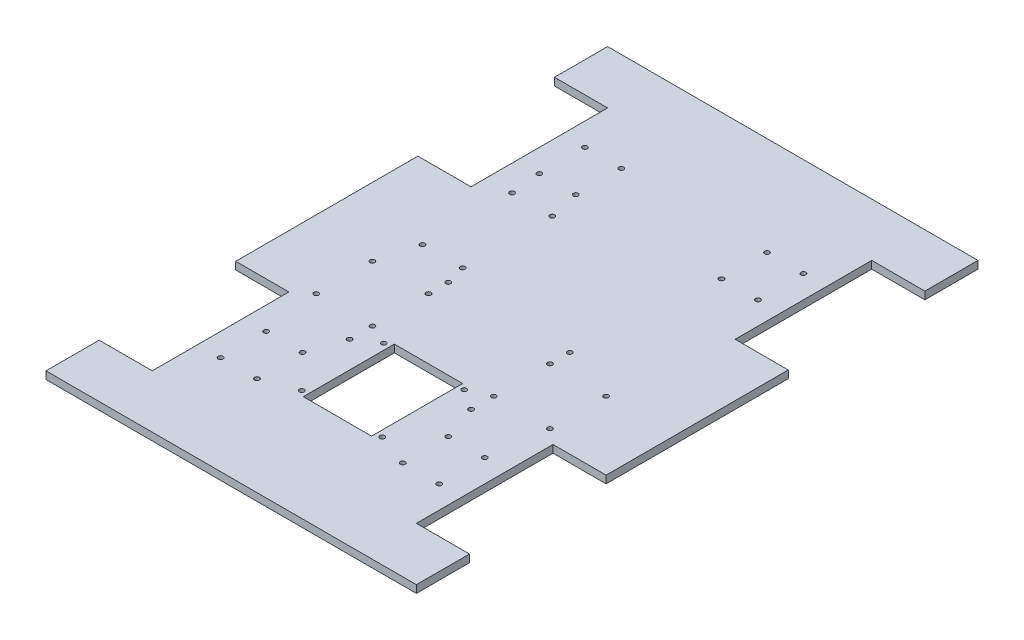
SolidWorks part; units mm, degrees
ref_plane "Front" through (0, 0, 0) normal (0, 0, 1) x (1, 0, 0)
ref_plane "Top" through (0, 0, 0) normal (0, 1, 0) x (1, 0, 0)
ref_plane "Right" through (0, 0, 0) normal (1, 0, 0) x (0, 0, -1)
sketch "草图2" plane through (0, 0, 0) normal (0, 1, 0) x (1, 0, 0)
  line L1 (0, 0) -> (160, 0)
  line L2 (0, 0) -> (0, 250)
  line L3 (0, 250) -> (160, 250)
  line L4 (160, 0) -> (160, 250)
  dimension "D1" = 250
  dimension "D2" = 160
extrude "原型板" add sketch "草图2" along normal blind 5
sketch "轮组位置" plane through (0, 5, 0) normal (0, 1, 0) x (1, 0, 0)
  line L0 (0, 250) -> (0, 0) construction
  line L1 (8, 245) -> (32, 245)
  line L2 (8, 245) -> (8, 215)
  line L3 (8, 215) -> (32, 215)
  line L4 (32, 245) -> (32, 215)
  line L5 (8, 35) -> (32, 35)
  line L6 (8, 35) -> (8, 5)
  line L7 (8, 5) -> (32, 5)
  line L8 (32, 35) -> (32, 5)
  line L9 (128, 245) -> (152, 245)
  line L10 (128, 245) -> (128, 215)
  line L11 (128, 215) -> (152, 215)
  line L12 (152, 245) -> (152, 215)
  line L13 (128, 35) -> (152, 35)
  line L14 (128, 35) -> (128, 5)
  line L15 (128, 5) -> (152, 5)
  line L16 (152, 35) -> (152, 5)
  line L17 (160, 0) -> (160, 250) construction
  line L19 (-11, 262.5) -> (-39, 262.5)
  line L20 (-11, 262.5) -> (-11, 197.5)
  line L21 (-11, 197.5) -> (-39, 197.5)
  line L22 (-39, 262.5) -> (-39, 197.5)
  line L23 (171, 262.5) -> (199, 262.5)
  line L24 (171, 262.5) -> (171, 197.5)
  line L25 (171, 197.5) -> (199, 197.5)
  line L26 (199, 262.5) -> (199, 197.5)
  line L27 (-11, 52.5) -> (-39, 52.5)
  line L28 (-11, 52.5) -> (-11, -12.5)
  line L29 (-11, -12.5) -> (-39, -12.5)
  line L30 (-39, 52.5) -> (-39, -12.5)
  line L31 (199, 52.5) -> (171, 52.5)
  line L32 (199, 52.5) -> (199, -12.5)
  line L33 (199, -12.5) -> (171, -12.5)
  line L34 (171, 52.5) -> (171, -12.5)
  point P24 (8, 230)
  point P25 (-11, 230)
  point P34 (8, 20)
  point P35 (-39, 20)
  point P40 (-25, 262.5)
  point P41 (20, 245)
  point P42 (140, 245)
  point P43 (185, 262.5)
  point P44 (-25, 52.5)
  point P45 (20, 35)
  point P46 (185, 52.5)
  point P47 (140, 35)
  point P49 (-11, 20)
  point P50 (0, 125)
  dimension "D1" = 30
  dimension "D2" = 24
  dimension "D3" = 30
  dimension "D4" = 24
  dimension "D5" = 30
  dimension "D6" = 24
  dimension "D7" = 30
  dimension "D8" = 24
  dimension "D9" = 8
  dimension "D10" = 8
  dimension "D11" = 8
  dimension "D12" = 8
  dimension "D13" = 0
  dimension "D14" = 0
  dimension "D15" = 28
  dimension "D16" = 65
  dimension "D17" = 0
  dimension "D18" = 28
  dimension "D19" = 65
  dimension "D20" = 0
  dimension "D21" = 45
  dimension "D22" = 45
  dimension "D23" = 45
  dimension "D24" = 45
  dimension "D25" = 28
  dimension "D26" = 105
  dimension "D27" = 0
  dimension "D28" = 0
  dimension "D29" = 28
  dimension "D30" = 65
  dimension "385" = 275
  dimension "D31" = 65
sketch "尺寸限制框" plane through (0, 0, 0) normal (0, 1, 0) x (1, 0, 0)
  line L0 (160, 250) -> (0, 250) construction
  line L1 (-55, 295) -> (215, 295)
  line L2 (-55, 295) -> (-55, -45)
  line L3 (-55, -45) -> (215, -45)
  line L4 (215, 295) -> (215, -45)
  line L5 (0, 250) -> (0, 0) construction
  point P4 (80, 295)
  point P7 (80, 250)
  point P8 (-55, 125)
  point P11 (0, 125)
  dimension "D1" = 340
  dimension "D2" = 270
  dimension "D3" = 0
  dimension "D4" = 0
sketch "草图6" plane through (0, 5, 0) normal (0, 1, 0) x (1, 0, 0)
  circle A0 centre (8, 245) radius 1.6
  circle A1 centre (32, 245) radius 1.6
  circle A2 centre (8, 215) radius 1.6
  circle A3 centre (32, 215) radius 1.6
  circle A4 centre (128, 245) radius 1.6
  circle A5 centre (152, 245) radius 1.6
  circle A6 centre (128, 215) radius 1.6
  circle A7 centre (152, 215) radius 1.6
  circle A8 centre (32, 35) radius 1.6
  circle A9 centre (8, 35) radius 1.6
  circle A10 centre (8, 5) radius 1.6
  circle A11 centre (32, 5) radius 1.6
  circle A12 centre (128, 35) radius 1.6
  circle A13 centre (152, 35) radius 1.6
  circle A14 centre (128, 5) radius 1.6
  circle A15 centre (152, 5) radius 1.6
  dimension "D1" = 3.2
  dimension "D2" = 3.2
  dimension "D3" = 3.2
  dimension "D4" = 3.2
  dimension "D5" = 3.2
  dimension "D6" = 3.2
  dimension "D7" = 3.2
  dimension "D8" = 3.2
  dimension "D9" = 3.2
  dimension "D10" = 3.2
  dimension "D11" = 3.2
  dimension "D12" = 3.2
  dimension "D13" = 3.2
  dimension "D14" = 3.2
  dimension "D15" = 3.2
  dimension "D16" = 3.2
extrude "轮组固定" cut sketch "草图6" against normal through all
sketch "草图7" plane through (0, 5, 0) normal (0, 1, 0) x (1, 0, 0)
  line L0 (0, 250) -> (0, 0) construction
  line L1 (160, 0) -> (160, 250) construction
  circle A0 centre (3, 110) radius 1.6
  circle A1 centre (40, 73) radius 1.6
  circle A2 centre (3, 73) radius 1.6
  circle A3 centre (40, 110) radius 1.6
  circle A4 centre (120, 110) radius 1.6
  circle A5 centre (157, 73) radius 1.6
  circle A6 centre (120, 73) radius 1.6
  circle A7 centre (157, 110) radius 1.6
  point P20 (0, 125)
  point P21 (160, 125)
  dimension "D1" = 37
  dimension "D2" = 37
  dimension "D3" = 3
  dimension "D4" = 37
  dimension "D5" = 37
  dimension "D6" = 37
  dimension "D7" = 37
  dimension "D8" = 3
  dimension "D9" = 37
  dimension "D10" = 0
  dimension "D11" = 37
  dimension "D12" = 0
  dimension "D13" = 0
  dimension "D14" = 15
  dimension "D15" = 15
  dimension "D16" = 0
extrude "L298N固定" cut sketch "草图7" against normal through all
sketch "草图9" plane through (0, 0, 0) normal (0, -1, 0) x (1, 0, 0)
  line L0 (160, -250) -> (0, -250) construction
  circle A1 centre (36.5, -195) radius 1.6
  circle A2 centre (10, -136) radius 1.6
  circle A3 centre (10, -195) radius 1.6
  circle A4 centre (36.5, -136) radius 1.6
  point P10 (80, -250)
  dimension "D1" = 26.5
  dimension "D2" = 59
  dimension "D3" = 0
  dimension "D4" = 0
  dimension "D5" = 0
  dimension "D6" = 0
  dimension "D7" = 70
  dimension "D8" = 3.2
  dimension "50" = 55
extrude "稳压模块固定" cut sketch "草图9" against normal blind 10
sketch "草图10" plane through (0, 0, 0) normal (0, -1, 0) x (1, 0, 0)
  line L0 (0, -250) -> (0, 0) construction
  line L1 (160, 0) -> (160, -250) construction
  circle A0 centre (40, -123) radius 1.6
  circle A1 centre (120, -123) radius 1.6
  circle A2 centre (40, -58) radius 1.6
  circle A3 centre (120, -58) radius 1.6
  point P4 (0, -125)
  dimension "D1" = 2
  dimension "D3" = 40
  dimension "D4" = 0
  dimension "D5" = 0
  dimension "D6" = 65
  dimension "D7" = 0
  dimension "D8" = 0
  dimension "D2" = 40
extrude "电池固定" cut sketch "草图10" against normal through all
sketch "草图11" plane through (0, 5, 0) normal (0, 1, 0) x (1, 0, 0)
  line L0 (0, 0) -> (160, 0) construction
  line L1 (102.5, 10) -> (57.5, 10)
  line L2 (102.5, 10) -> (102.5, 70)
  line L3 (102.5, 70) -> (57.5, 70)
  line L4 (57.5, 10) -> (57.5, 70)
  point P4 (80, 10)
  point P7 (80, 0)
  dimension "D1" = 45
  dimension "D2" = 60
  dimension "D3" = 0
  dimension "D4" = 10
extrude "2560位置 " cut sketch "草图11" against normal through all
sketch "草图12" plane through (0, 5, 0) normal (0, 1, 0) x (1, 0, 0)
  line L0 (102.5, 10) -> (102.5, 70) construction
  line L1 (57.5, 10) -> (102.5, 10) construction
  line L2 (57.5, 70) -> (57.5, 10) construction
  line L3 (102.5, 70) -> (57.5, 70) construction
  circle A0 centre (106.5, 13) radius 1.6
  circle A1 centre (53.5, 67) radius 1.6
  circle A2 centre (106.5, 67) radius 1.6
  circle A3 centre (53.5, 13) radius 1.6
  dimension "D1" = 4
  dimension "D2" = 3
  dimension "D3" = 4
  dimension "D4" = 3
  dimension "D5" = 0
  dimension "D6" = 0
  dimension "D7" = 0
  dimension "D8" = 0
extrude "切除-拉伸2" cut sketch "草图12" against normal through all
sketch "草图13" plane through (0, 5, 0) normal (0, 1, 0) x (1, 0, 0)
  line L0 (0, 0) -> (160, 0) construction
  line L1 (202, -60) -> (-42, -60)
  line L2 (202, -60) -> (202, -25)
  line L3 (202, -25) -> (160, -25)
  line L4 (-42, -60) -> (-42, -25)
  line L5 (0, -25) -> (-42, -25)
  line L6 (160, 0) -> (0, 0)
  line L7 (160, 0) -> (160, -25)
  line L9 (0, 0) -> (0, -25)
  line L10 (160, 250) -> (0, 250) construction
  line L11 (202, 275) -> (160, 275)
  line L12 (202, 275) -> (202, 310)
  line L13 (202, 310) -> (-42, 310)
  line L14 (-42, 275) -> (-42, 310)
  line L15 (0, 275) -> (-42, 275)
  line L16 (160, 250) -> (0, 250)
  line L17 (160, 250) -> (160, 275)
  line L19 (0, 250) -> (0, 275)
  circle A1 centre (152, 35) radius 1.6 construction
  circle A2 centre (8, 35) radius 1.6 construction
  circle A3 centre (152, 245) radius 1.6 construction
  circle A4 centre (8, 245) radius 1.6 construction
  dimension "D2" = 50
  dimension "D1" = 25
  dimension "D3" = 35
  dimension "D4" = 50
  dimension "D5" = 35
  dimension "D6" = 50
  dimension "D7" = 50
  dimension "D8" = 25
extrude "凸台-拉伸1" add sketch "草图13" against normal blind 5
sketch "草图14" plane through (0, 5, 0) normal (0, 1, 0) x (1, 0, 0)
  line L1 (202, 65) -> (160, 65)
  line L2 (202, 65) -> (202, 185)
  line L3 (202, 185) -> (160, 185)
  line L4 (160, 65) -> (160, 185)
  line L5 (160, -25) -> (160, 275) construction
  line L6 (0, 275) -> (0, -25) construction
  line L7 (0, 65) -> (-42, 65)
  line L8 (0, 65) -> (0, 185)
  line L9 (0, 185) -> (-42, 185)
  line L10 (-42, 65) -> (-42, 185)
  circle A0 centre (152, 35) radius 1.6 construction
  circle A1 centre (152, 215) radius 1.6 construction
  circle A2 centre (8, 35) radius 1.6 construction
  circle A3 centre (8, 215) radius 1.6 construction
  point P16 (-21, 65)
  dimension "D1" = 42
  dimension "D2" = 0
  dimension "D3" = 30
  dimension "D4" = 30
  dimension "D5" = 42
  dimension "D6" = 0
  dimension "D7" = 30
  dimension "D8" = 30
extrude "凸台-拉伸2" add sketch "草图14" against normal blind 5
sketch "草图15" plane through (0, 5, 0) normal (0, 1, 0) x (1, 0, 0)
  line L0 (160, 65) -> (202, 65) construction
  line L1 (160, 275) -> (202, 275) construction
  line L2 (167, 65) -> (160, 65)
  line L3 (167, 65) -> (167, -25)
  line L4 (167, -25) -> (160, -25)
  line L5 (160, 65) -> (160, -25)
  line L6 (160, 185) -> (167, 185)
  line L7 (160, 185) -> (160, 275)
  line L8 (160, 275) -> (167, 275)
  line L9 (167, 185) -> (167, 275)
  line L10 (-42, 65) -> (0, 65) construction
  line L11 (0, -25) -> (-7, -25)
  line L12 (0, -25) -> (0, 65)
  line L13 (0, 65) -> (-7, 65)
  line L14 (-7, -25) -> (-7, 65)
  line L15 (-42, 275) -> (0, 275) construction
  line L16 (0, 185) -> (-7, 185)
  line L17 (0, 185) -> (0, 275)
  line L18 (0, 275) -> (-7, 275)
  line L19 (-7, 185) -> (-7, 275)
  dimension "D1" = 7
  dimension "D2" = 7
  dimension "D3" = 7
  dimension "D4" = 7
extrude "凸台-拉伸3" add sketch "草图15" against normal blind 5
equation "\"7。5\"=7.01277"
